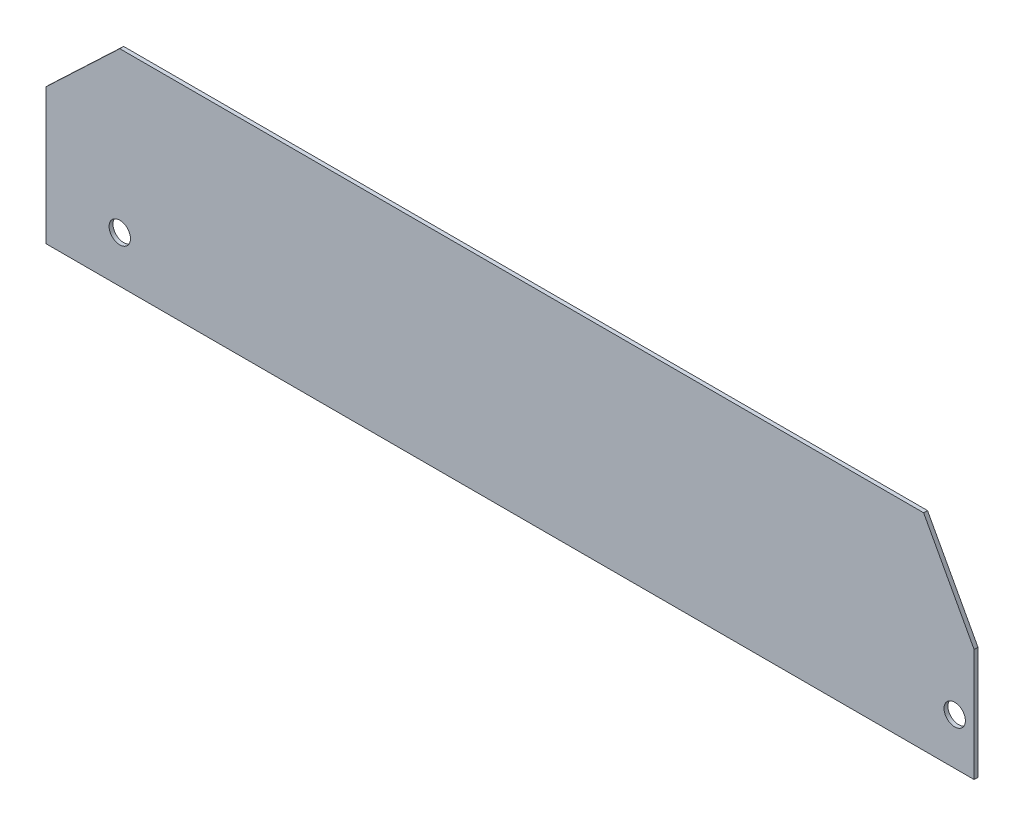
SolidWorks part; units mm, degrees
ref_plane "Front Plane" through (0, 0, 0) normal (0, 0, 1) x (1, 0, 0)
ref_plane "Top Plane" through (0, 0, 0) normal (0, 1, 0) x (1, 0, 0)
ref_plane "Right Plane" through (0, 0, 0) normal (1, 0, 0) x (0, 0, -1)
sketch "Side wall with M5 attachments profile" plane through (0, 0, 0) normal (0, 0, 1) x (1, 0, 0)
  line L0 (-136, 7) -> (103, 7)
  line L1 (103, 7) -> (103, 36)
  line L2 (103, 36) -> (90, 60)
  line L3 (90, 60) -> (-117, 60)
  line L4 (-117, 60) -> (-136, 42)
  line L5 (-136, 42) -> (-136, 7)
  circle A0 centre (-117, 19) radius 2.75
  circle A1 centre (98, 19) radius 2.75
extrude "Side wall with M5 attachments" add sketch "Side wall with M5 attachments profile" along normal blind 1
